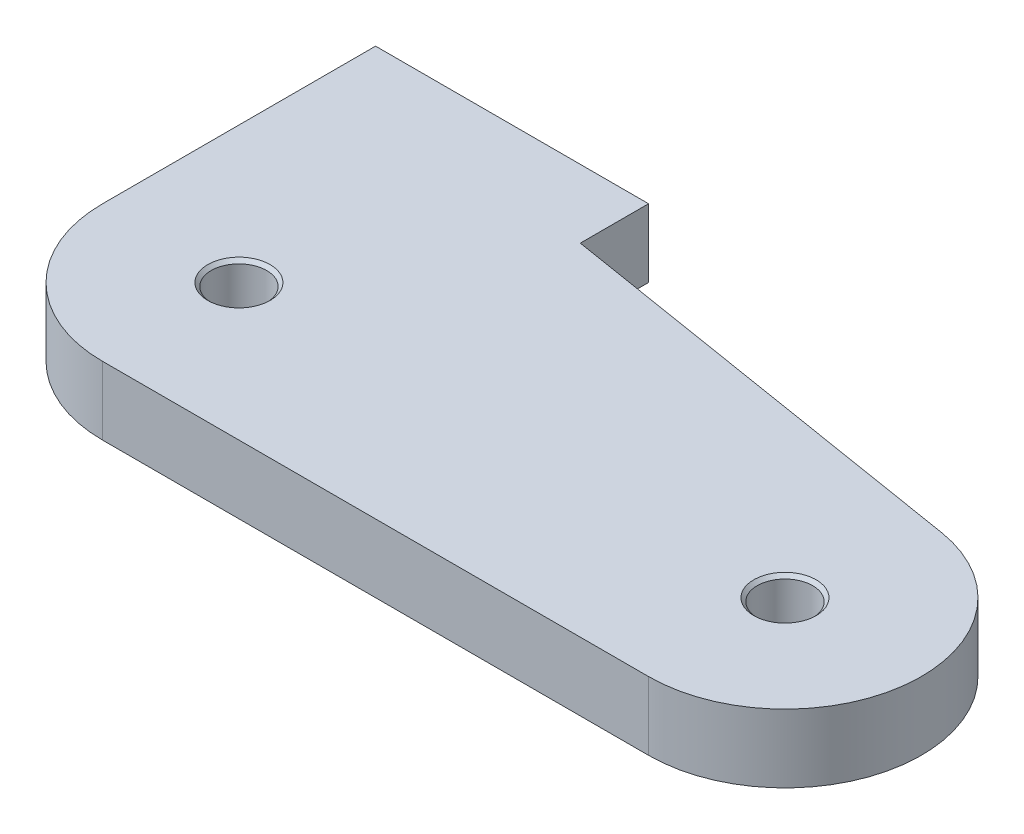
SolidWorks part; units mm, degrees
ref_plane "Front Plane" through (0, 0, 0) normal (0, 0, 1) x (1, 0, 0)
ref_plane "Top Plane" through (0, 0, 0) normal (0, 1, 0) x (1, 0, 0)
ref_plane "Right Plane" through (0, 0, 0) normal (1, 0, 0) x (0, 0, -1)
sketch "Sketch1" plane through (0, 0, 0) normal (0, 1, 0) x (1, 0, 0)
  line L0 (0, 0) -> (101.6, 0)
  line L2 (-25.3862, 25.3957) -> (-25.3862, 76.2)
  line L3 (-25.3862, 76.2) -> (25.4138, 76.2)
  line L4 (25.4138, 76.2) -> (25.4138, 63.5)
  line L5 (25.4138, 63.5) -> (105.67, 50.4718)
  arc A0 (101.6, 0) -> (105.67, 50.4718) centre (101.6, 25.4) ccw
  arc A1 (-25.3862, 25.3957) -> (0, 0) centre (0, 25.3862) ccw
  point P7 (0, 0)
  point P11 (0, 0)
  dimension "D2" = 25.4
  dimension "D3" = 25.3862
  dimension "D1" = 101.6
  dimension "D4" = 76.2
  dimension "D5" = 50.8043
  dimension "D6" = 12.7
  dimension "D7" = 50.8
extrude "Boss-Extrude2" add sketch "Sketch1" along normal blind 12.7
sketch "Sketch16" plane through (0, 12.7, 0) normal (0, 1, 0) x (1, 0, 0)
  point P0 (101.6, 25.4)
hole_wizard "13/32 (0.40625) Diameter Hole3" positions "Sketch16" profile "Sketch17" hole size "13/32" standard "ANSI Inch" end condition through all
sketch "Sketch17" plane through (101.6, 12.7, -25.4) normal (1, 0, 0) x (0, 0, 1)
  line L0 (0, 0) -> (0, 12.7)
  line L1 (0, 12.7) -> (5.1594, 12.7)
  line L2 (5.1594, 12.7) -> (5.1594, 0.635)
  line L3 (5.1594, 0.635) -> (5.7944, 0)
  line L5 (5.7944, 0) -> (0, 0)
  line L6 (-5.1594, 0.635) -> (-5.7944, 0) construction
  line L11 (0, -6.35) -> (0, 107.95) construction
  dimension "Thru Hole Dia." = 10.3187
  dimension "Thru Hole Depth" = 12.7
  dimension "Near C'Sink Dia." = 11.5887
  dimension "Near C'Sink Angle" = 90
sketch "Sketch18" plane through (0, 12.7, 0) normal (0, 1, 0) x (1, 0, 0)
  point P0 (0, 25.3862)
hole_wizard "13/32 (0.40625) Diameter Hole2" positions "Sketch18" profile "Sketch19" hole size "13/32" standard "ANSI Inch" end condition through all
sketch "Sketch19" plane through (0, 12.7, -25.3862) normal (1, 0, 0) x (0, 0, 1)
  line L0 (0, 0) -> (0, 12.7)
  line L1 (0, 12.7) -> (5.1594, 12.7)
  line L2 (5.1594, 12.7) -> (5.1594, 0.635)
  line L3 (5.1594, 0.635) -> (5.7944, 0)
  line L5 (5.7944, 0) -> (0, 0)
  line L6 (-5.1594, 0.635) -> (-5.7944, 0) construction
  line L11 (0, -6.35) -> (0, 107.95) construction
  dimension "Thru Hole Dia." = 10.3187
  dimension "Thru Hole Depth" = 12.7
  dimension "Near C'Sink Dia." = 11.5887
  dimension "Near C'Sink Angle" = 90
